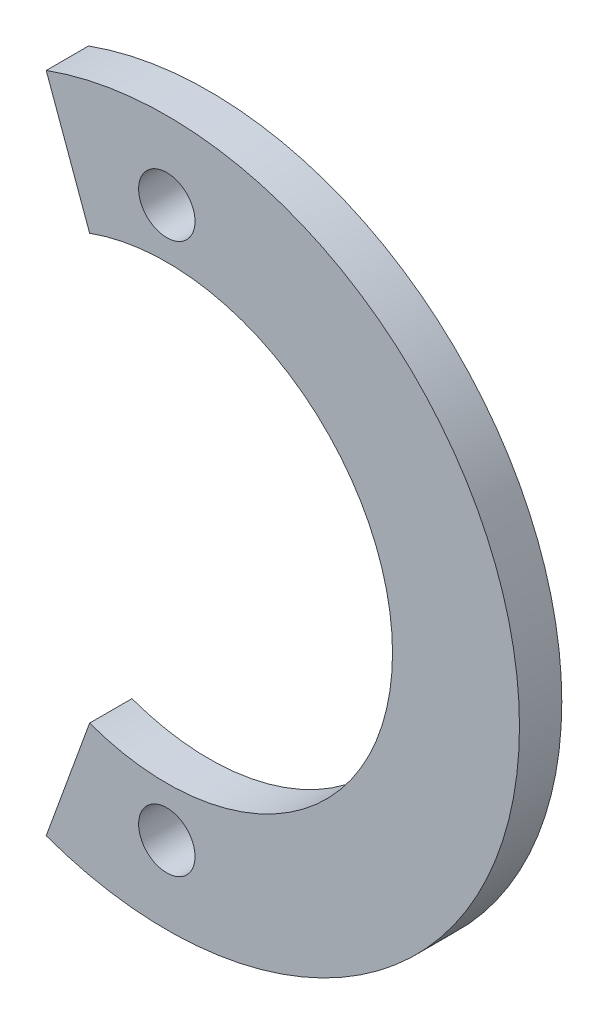
SolidWorks part; units mm, degrees
ref_plane "Alzado" through (0, 0, 0) normal (0, 0, 1) x (1, 0, 0)
ref_plane "Planta" through (0, 0, 0) normal (0, 1, 0) x (1, 0, 0)
ref_plane "Vista lateral" through (0, 0, 0) normal (1, 0, 0) x (0, 0, -1)
sketch "Croquis1" plane through (0, 0, 0) normal (0, 0, 1) x (1, 0, 0)
  line L0 (0, 0) -> (-8.5505, -23.4923)
  line L1 (0, 0) -> (-8.5505, 23.4923)
  line L2 (0, 0) -> (-35.9411, 0) construction
  circle A0 centre (0, 0) radius 25
  circle A1 centre (0, 0) radius 16
  dimension "D1" = 50
  dimension "D2" = 32
  dimension "D3" = 70
  dimension "D4" = 70
extrude "Saliente-Extruir1" add sketch "Croquis1" along normal blind 3 contours A1 L0 A0 L1
sketch "Croquis2" plane through (0, 0, 0) normal (0, 0, -1) x (-1, 0, 0)
  line L0 (0, 0) -> (0, 25) construction
  line L1 (0, 0) -> (0, -16) construction
  line L2 (0, -16) -> (0, -25) construction
  line L3 (0, 0) -> (10.5438, 0) construction
  arc A0 (8.5505, 23.4923) -> (8.5505, -23.4923) centre (0, 0) ccw construction
  arc A1 (5.4723, 15.0351) -> (5.4723, -15.0351) centre (0, 0) ccw construction
  circle A2 centre (0, -19.5) radius 2
  circle A3 centre (0, 19.5) radius 2
  point P17 (0, 0)
  dimension "D1" = 4
  dimension "D2" = 19.5
extrude "Cortar-Extruir1" cut sketch "Croquis2" against normal blind 3
